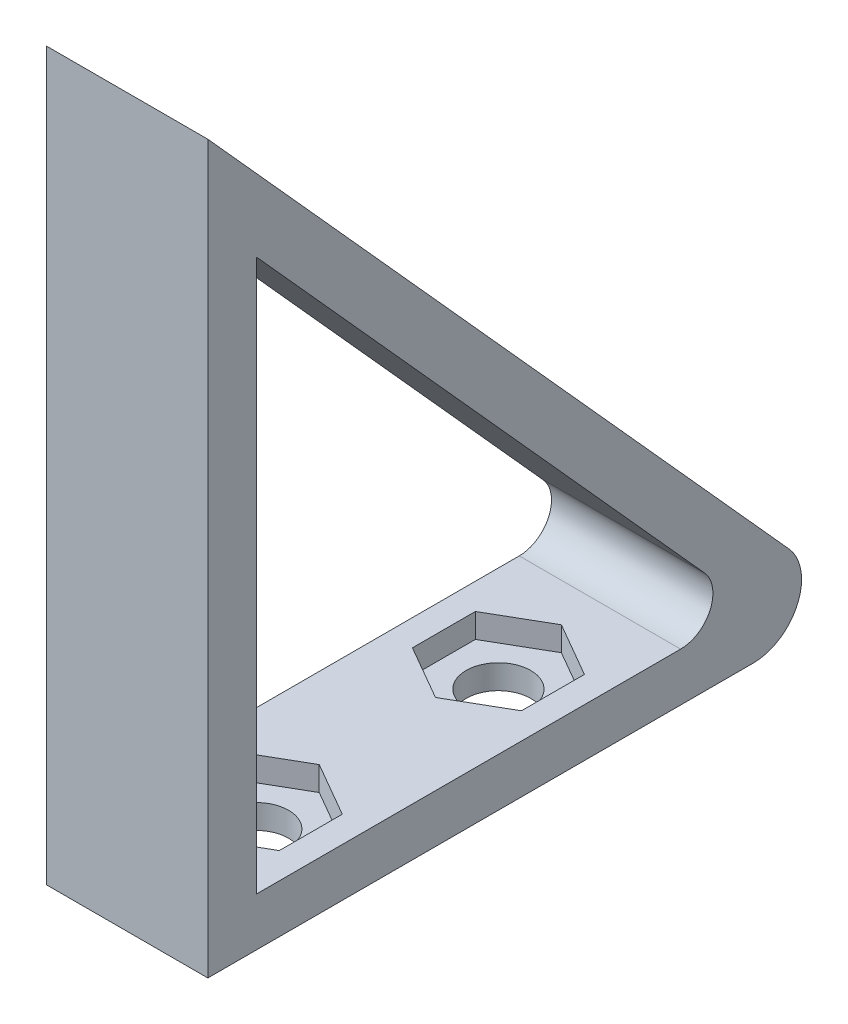
SolidWorks part; units mm, degrees
ref_plane "前视基准面" through (0, 0, 0) normal (0, 0, 1) x (1, 0, 0)
ref_plane "上视基准面" through (0, 0, 0) normal (0, 1, 0) x (1, 0, 0)
ref_plane "右视基准面" through (0, 0, 0) normal (1, 0, 0) x (0, 0, -1)
sketch "Sketch1" plane through (0, 0, 0) normal (1, 0, 0) x (0, 0, -1)
  line L0 (0, 0) -> (0, 45)
  line L1 (0, 45) -> (40.5182, 0)
  line L2 (40.5182, 0) -> (0, 0)
  dimension "D1" = 45
  dimension "D2" = 42
extrude "Boss-Extrude1" add sketch "Sketch1" against normal blind 10
sketch "Sketch2" plane through (0, 0, 0) normal (1, 0, 0) x (0, 0, -1)
  line L0 (0, 45) -> (0, 0) construction
  line L1 (0, 0) -> (40.5182, 0) construction
  line L2 (40.5182, 0) -> (0, 45) construction
  line L3 (33.7801, 3) -> (3, 37.1847)
  line L4 (3, 37.1847) -> (3, 3)
  line L5 (3, 3) -> (33.7801, 3)
  dimension "D1" = 3
extrude "Cut-Extrude1" cut sketch "Sketch2" against normal through all
sketch "Sketch3" plane through (0, 0, 0) normal (0, -1, 0) x (1, 0, 0)
  line L0 (-5, 0.607) -> (-5, -34.9882) construction
  line L1 (-10, 0) -> (-10, -40.5182) construction
  line L2 (-10, 0) -> (0, 0) construction
  circle A0 centre (-5, -8) radius 2
  circle A1 centre (-5, -23) radius 2
  dimension "D2" = 4
  dimension "D3" = 4
  dimension "D1" = 5
  dimension "D4" = 15
  dimension "D5" = 8
extrude "Cut-Extrude2" cut sketch "Sketch3" against normal blind 3
sketch "Sketch4" plane through (0, 3, 0) normal (0, 1, 0) x (1, 0, 0)
  line L0 (-10, 3) -> (-10, 33.7801) construction
  line L1 (-5, 19.1) -> (-1.6225, 21.05)
  line L2 (-1.6225, 21.05) -> (-1.6225, 24.95)
  line L3 (-1.6225, 24.95) -> (-5, 26.9)
  line L4 (-5, 26.9) -> (-8.3775, 24.95)
  line L5 (-8.3775, 24.95) -> (-8.3775, 21.05)
  line L6 (-8.3775, 21.05) -> (-5, 19.1)
  line L7 (-5, 11.9) -> (-8.3775, 9.95)
  line L8 (-8.3775, 9.95) -> (-8.3775, 6.05)
  line L9 (-8.3775, 6.05) -> (-5, 4.1)
  line L10 (-5, 4.1) -> (-1.6225, 6.05)
  line L11 (-1.6225, 6.05) -> (-1.6225, 9.95)
  line L12 (-1.6225, 9.95) -> (-5, 11.9)
  circle A0 centre (-5, 23) radius 3.3775 construction
  circle A1 centre (-5, 8) radius 3.3775 construction
  dimension "D1" = 7.8
  dimension "D2" = 7.8
extrude "Cut-Extrude3" cut sketch "Sketch4" against normal blind 1.5
fillet "Fillet1" radius 3 1 edges at (-5, 0, -40.5182)
fillet "Fillet2" radius 2 1 edges at (-5, 3, -33.7801)
